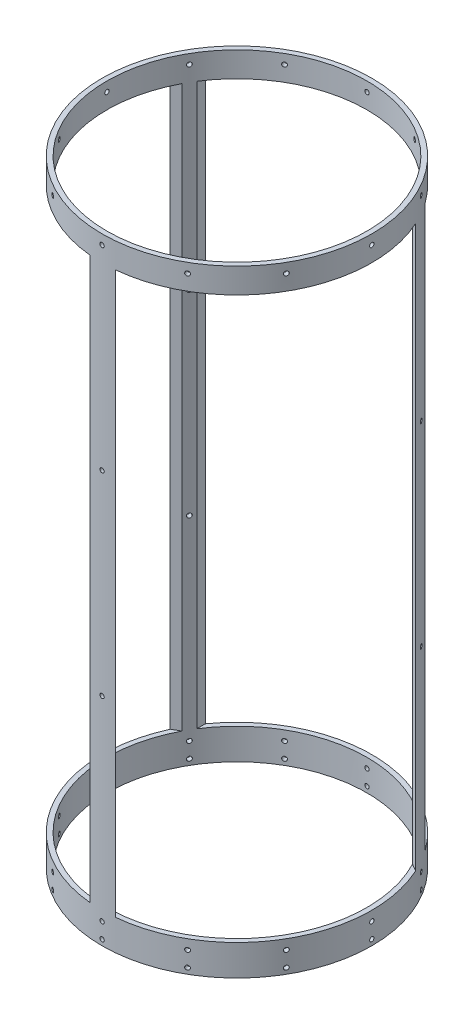
SolidWorks part; units mm, degrees
material "6061-T6 (SS)"
ref_plane "Front Plane" through (0, 0, 0) normal (0, 0, 1) x (1, 0, 0)
ref_plane "Top Plane" through (0, 0, 0) normal (0, 1, 0) x (1, 0, 0)
ref_plane "Right Plane" through (0, 0, 0) normal (1, 0, 0) x (0, 0, -1)
sketch "Sketch1" plane through (0, 0, 0) normal (0, 1, 0) x (1, 0, 0)
  circle A0 centre (0, 0) radius 88.9
  circle A1 centre (0, 0) radius 85.725
  dimension "D1" = 177.8
  dimension "D2" = 171.45
extrude "Boss-Extrude1" add sketch "Sketch1" along normal mid plane 406.4
sketch "Sketch2" plane through (0, 0, 0) normal (0, 0, 1) x (1, 0, 0)
  line L0 (85.725, 203.2) -> (-85.725, 203.2) construction
  line L1 (-72.39, -182.88) -> (72.39, -182.88)
  line L2 (-72.39, -182.88) -> (-72.39, 186.69)
  line L3 (-72.39, 186.69) -> (72.39, 186.69)
  line L4 (72.39, -182.88) -> (72.39, 186.69)
  line L5 (-72.39, -182.88) -> (72.39, 186.69) construction
  line L6 (-72.39, 186.69) -> (72.39, -182.88) construction
  line L7 (88.9, -203.2) -> (88.9, 203.2) construction
  line L8 (-88.9, 203.2) -> (-88.9, -203.2) construction
  line L9 (-88.9, -203.2) -> (88.9, -203.2) construction
  point P0 (0, 0)
  dimension "D1" = 16.51
  dimension "D2" = 16.51
  dimension "D3" = 16.51
  dimension "D4" = 20.32
extrude "Cut-Extrude1" cut sketch "Sketch2" against normal up to surface (51.6033 mm away)
pattern_circular "CirPattern1" count 3 over 360 about axis through (0, 0, 0) along (0, 1, 0) of "Cut-Extrude1"
ref_plane "Plane1" through (88.9, 0, 0) normal (1, 0, 0) x (0, 0, -1)
sketch "Sketch3" plane through (88.9, 0, 0) normal (1, 0, 0) x (0, 0, -1)
  line L0 (36.8899, -182.88) -> (-88.4932, -182.88) construction
  line L1 (-88.9, -203.2) -> (88.9, -203.2) construction
  circle A0 centre (0, -199.39) radius 1.4351
  circle A1 centre (0, -189.23) radius 1.4351
  dimension "D1" = 3.81
  dimension "D2" = 2.8702
  dimension "D3" = 2.8702
  dimension "D4" = 6.35
extrude "Cut-Extrude2" cut sketch "Sketch3" against normal blind 15.24
pattern_circular "CirPattern2" count 12 over 360 about axis through (0, 203.2, 0) along (0, -1, 0) of "Cut-Extrude2"
sketch "Sketch4" plane through (88.9, 0, 0) normal (1, 0, 0) x (0, 0, -1)
  line L0 (0, 97.79) -> (0, -97.79) construction
  line L1 (88.9, 203.2) -> (-88.9, 203.2) construction
  circle A0 centre (0, 196.85) radius 1.4351
  dimension "D1" = 2.8702
  dimension "D2" = 6.35
extrude "Cut-Extrude3" cut sketch "Sketch4" against normal blind 15.24
pattern_circular "CirPattern3" count 12 over 360 about axis through (0, 203.2, 0) along (0, -1, 0) of "Cut-Extrude3"
ref_plane "Plane2" through (0, 0, 88.9) normal (0, 0, 1) x (1, 0, 0)
sketch "Sketch5" plane through (0, 0, 88.9) normal (0, 0, 1) x (1, 0, 0)
  circle A0 centre (0, 68.1736) radius 1.4351
  circle A1 centre (0, -60.5536) radius 1.4351
  circle A2 centre (0, 196.85) radius 1.4351 construction
  circle A3 centre (0, -189.23) radius 1.4351 construction
  dimension "D1" = 128.6764
  dimension "D2" = 128.6764
  dimension "D3" = 2.8702
  dimension "D4" = 2.8702
extrude "Cut-Extrude4" cut sketch "Sketch5" against normal blind 35.56
pattern_circular "CirPattern4" count 3 over 360 about axis through (0, 203.2, 0) along (0, -1, 0) of "Cut-Extrude4"
